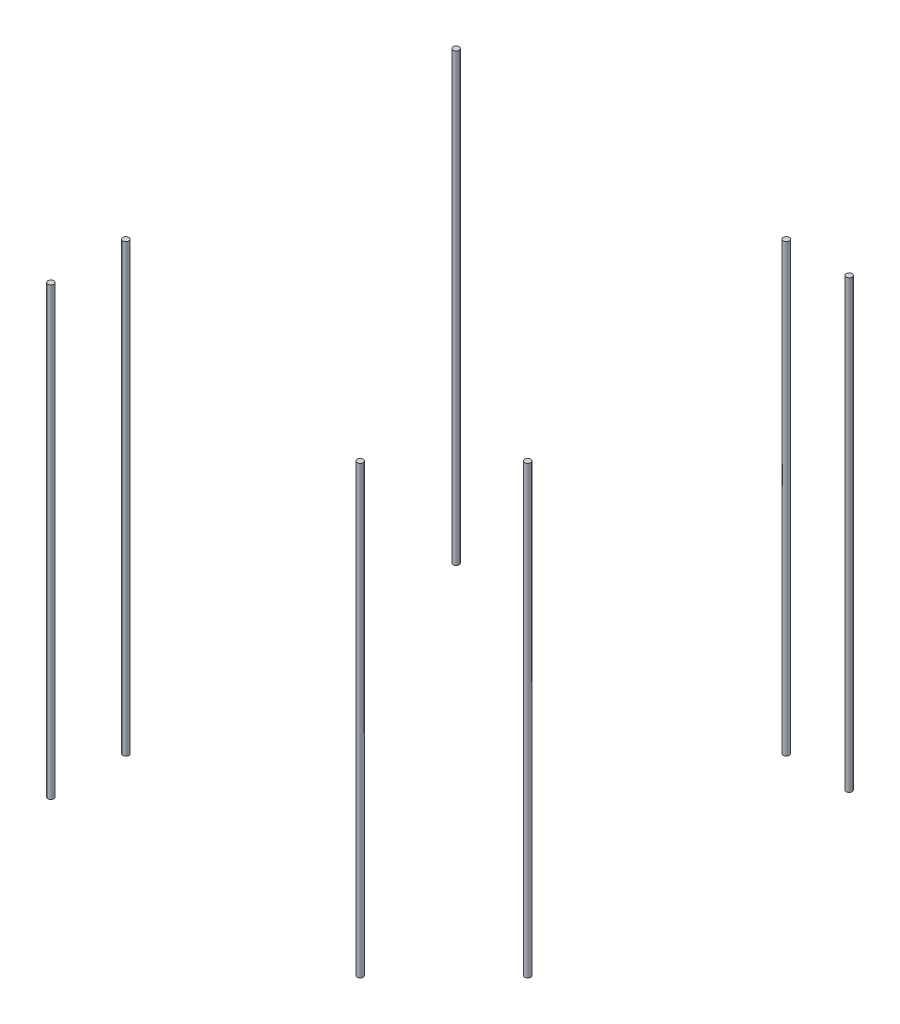
SolidWorks part; units mm, degrees
material "AISI 1020"
ref_plane "Спереди" through (0, 0, 0) normal (0, 0, 1) x (1, 0, 0)
ref_plane "Сверху" through (0, 0, 0) normal (0, 1, 0) x (1, 0, 0)
ref_plane "Справа" through (0, 0, 0) normal (1, 0, 0) x (0, 0, -1)
sketch "Эскиз1" plane through (0, 0, 0) normal (0, 1, 0) x (1, 0, 0)
  line L0 (6, -338) -> (-6, -338) construction
  line L1 (6, -338) -> (6, 350) construction
  line L9 (-350, -6) -> (338, -6) construction
  line L14 (338, -6) -> (338, 6) construction
  line L22 (-350, -6) -> (338, -6) construction
  line L27 (412, -329.2893) -> (400, -329.2893) construction
  line L28 (400, 350) -> (400, -329.2893) construction
  line L29 (317.2893, -412) -> (-362, -412) construction
  line L30 (317.2893, -424) -> (317.2893, -412) construction
  line L36 (-350, -6) -> (338, -6) construction
  circle A0 centre (335, -9) radius 3
  circle A1 centre (9, -9) radius 3
  circle A2 centre (9, -335) radius 3
  circle A3 centre (314.2893, -409) radius 3
  circle A4 centre (397, -326.2893) radius 3
  circle A5 centre (9, -409) radius 3
  circle A6 centre (397, -9) radius 3
  dimension "D1" = 6
extrude "Бобышка-Вытянуть1" add sketch "Эскиз1" along normal blind 20 and the other way blind 420
